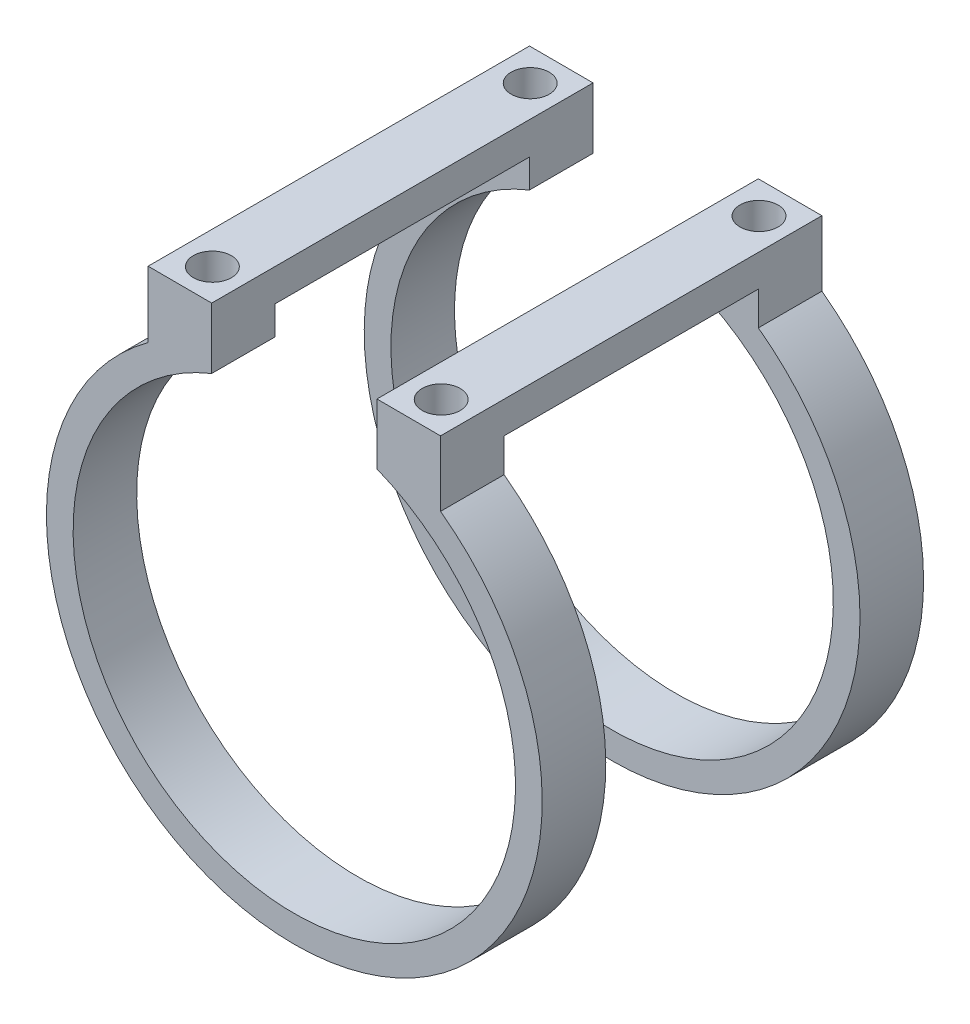
SolidWorks part; units mm, degrees
ref_plane "Alzado" through (0, 0, 0) normal (0, 0, 1) x (1, 0, 0)
ref_plane "Planta" through (0, 0, 0) normal (0, 1, 0) x (1, 0, 0)
ref_plane "Vista lateral" through (0, 0, 0) normal (1, 0, 0) x (0, 0, -1)
sketch "Croquis1" plane through (0, 0, 0) normal (0, 0, 1) x (1, 0, 0)
  line L8 (0, 0) -> (0, 15.9223) construction
  line L9 (0, 20.9223) -> (0, 17.9223) construction
  line L22 (0, 17.9223) -> (0, 15.9223) construction
  line L23 (6.5, 17.9223) -> (-6.5, 17.9223) construction
  line L24 (-6.5, 20.9389) -> (-6.5, 16.1403)
  line L25 (6.5, 20.9057) -> (6.5, 16.1403)
  line L27 (-11.5, 20.9517) -> (-11.5, 15.748)
  line L29 (11.5, 20.8929) -> (11.5, 15.748)
  line L30 (-11.5, 20.9517) -> (-6.5, 20.9389)
  line L32 (11.5, 20.8929) -> (6.5, 20.9057)
  line L33 (-17.4, 0) -> (-19.5, 0) construction
  arc A6 (-11.5, 15.748) -> (11.5, 15.748) centre (0, 0) ccw
  arc A7 (-6.5, 16.1403) -> (6.5, 16.1403) centre (0, 0) ccw
  point P8 (0, 0)
  point P9 (0, 0)
  point P20 (0, 17.9223)
  dimension "D3" = 17.4
  dimension "D2" = 5
  dimension "D4" = 2
  dimension "D5" = 13
  dimension "D9" = 5
extrude "Saliente-Extruir1" add sketch "Croquis1" along normal blind 30
sketch "Croquis3" plane through (0, 0, 0) normal (1, 0, 0) x (0, 0, -1)
  line L0 (-30, 18.3929) -> (-25, 18.3929) construction
  line L2 (-25, 18.3929) -> (-5, 18.3929) construction
  line L3 (-5, 18.3929) -> (0, 18.3929) construction
  line L6 (-25, 18.3929) -> (-25, -22.4)
  line L8 (-25, -22.4) -> (-5, -22.4)
  line L9 (-5, -22.4) -> (-5, 18.3929)
  line L10 (-5, 18.3929) -> (-25, 18.3929)
  line L11 (-30, 20.8929) -> (0, 20.8929) construction
  point P2 (0, 0)
  point P7 (0, 0)
  point P9 (0, 0)
  point P10 (0, 0)
  dimension "D1" = 5
  dimension "D2" = 2.5
extrude "Cortar-Extruir2" cut sketch "Croquis3" against normal through all both and the other way through all
sketch "Croquis4" plane through (0.0535, 20.9221, 0) normal (0.0026, 1, 0) x (1, -0.0026, 0)
  line L0 (8.9465, 0) -> (8.9465, -5) construction
  line L1 (11.4465, 0) -> (6.4465, 0) construction
  line L3 (0, 0) -> (0, -15) construction
  line L4 (0, -15) -> (6.4465, -15) construction
  line L5 (6.4465, -30) -> (6.4465, 0) construction
  circle A0 centre (9, -2.5) radius 1.5
  circle A1 centre (-9, -2.5) radius 1.5
  circle A2 centre (-9, -27.5) radius 1.5
  circle A3 centre (9, -27.5) radius 1.5
  point P7 (8.9465, -2.5)
  dimension "D3" = 3
  dimension "D2" = 5
  dimension "D4" = 18
extrude "Cortar-Extruir3" cut sketch "Croquis4" against normal blind 10 and the other way through all
